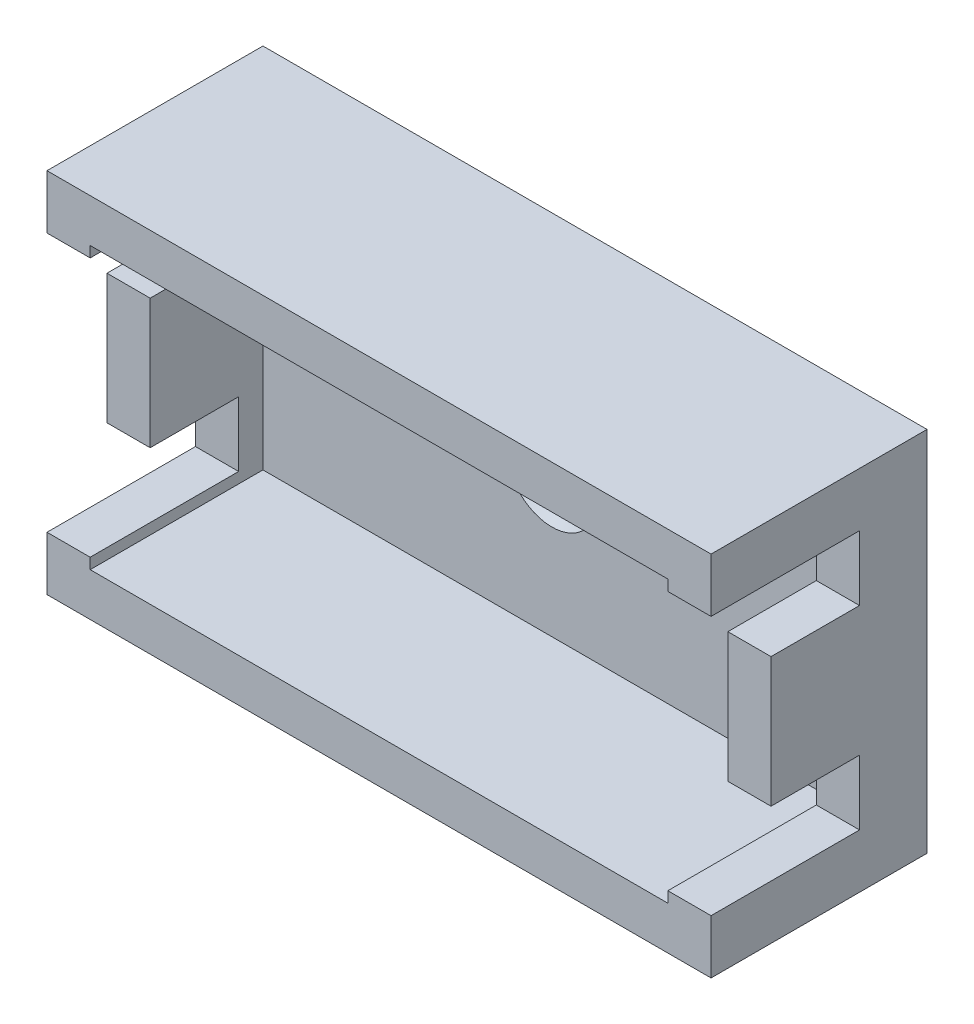
SolidWorks part; units mm, degrees
ref_plane "Piano frontale" through (0, 0, 0) normal (0, 0, 1) x (1, 0, 0)
ref_plane "Piano superiore" through (0, 0, 0) normal (0, 1, 0) x (1, 0, 0)
ref_plane "Piano destro" through (0, 0, 0) normal (1, 0, 0) x (0, 0, -1)
sketch "Schizzo1" plane through (0, 0, 0) normal (0, 0, 1) x (1, 0, 0)
  line L1 (0, 0) -> (-53.5, 0)
  line L2 (0, 0) -> (0, 26)
  line L3 (0, 26) -> (-53.5, 26)
  line L4 (-53.5, 0) -> (-53.5, 26)
  dimension "D1" = 53.5
  dimension "D2" = 26
extrude "Estrusione-Sottile1" add sketch "Schizzo1" along normal blind 20 thin thin type one direction wall 4
sketch "Schizzo2" plane through (0, 0, 0) normal (0, 0, 1) x (1, 0, 0)
  line L1 (0, 0) -> (-53.5, 0)
  line L2 (0, 0) -> (0, 26)
  line L3 (0, 26) -> (-53.5, 26)
  line L4 (-53.5, 0) -> (-53.5, 26)
extrude "Estrusione-Estrusione1" add sketch "Schizzo2" along normal blind 4
sketch "Schizzo3" plane through (0, 0, 4) normal (0, 0, 1) x (1, 0, 0)
  line L2 (-53.5, 26) -> (0, 0) construction
  line L3 (0, 26) -> (-53.5, 0) construction
  circle A0 centre (-26.75, 13) radius 2
  dimension "D1" = 4
extrude "Taglio-Estrusione1" cut sketch "Schizzo3" against normal blind 4
sketch "Schizzo4" plane through (-57.5, 0, 0) normal (-1, 0, 0) x (0, 0, 1)
  line L0 (20, 30) -> (20, -4) construction
  line L1 (20, 25) -> (6.2502, 25)
  line L2 (20, 25) -> (20, 27)
  line L3 (14.4457, 19) -> (6.2502, 19)
  line L4 (6.2502, 25) -> (6.2502, 19)
  line L5 (20, 30) -> (0, 30) construction
  line L6 (20, 13) -> (0, 13) construction
  line L7 (0, 30) -> (0, -4) construction
  line L8 (20, 1) -> (20, -1)
  line L9 (14.4457, 7) -> (6.2502, 7)
  line L10 (6.2502, 1) -> (6.2502, 7)
  line L11 (20, 1) -> (6.2502, 1)
  line L12 (14.4457, 19) -> (14.4457, 7)
  dimension "D1" = 5
  dimension "D2" = 6
extrude "Taglio-Estrusione3" cut sketch "Schizzo4" against normal through all
chamfer "Smusso1" distance 2.2 angle 45 1 edges at (-24.75, 13, 4)
